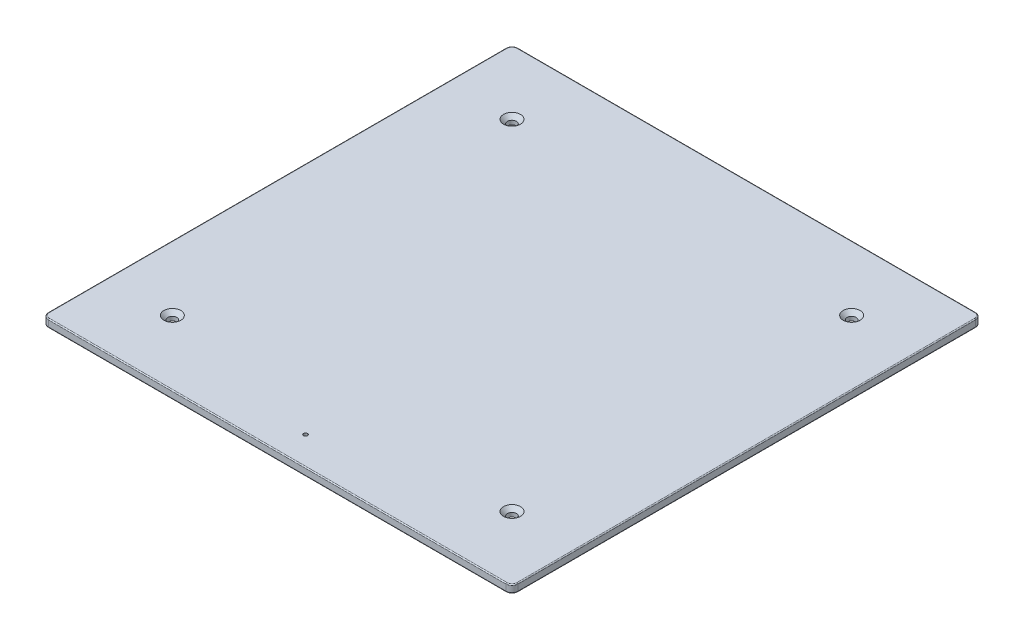
SolidWorks part; units mm, degrees
ref_plane "Front Plane" through (0, 0, 0) normal (0, 0, 1) x (1, 0, 0)
ref_plane "Top Plane" through (0, 0, 0) normal (0, 1, 0) x (1, 0, 0)
ref_plane "Right Plane" through (0, 0, 0) normal (1, 0, 0) x (0, 0, -1)
sketch "Sketch1" plane through (0, 0, 0) normal (0, 1, 0) x (1, 0, 0)
  line L1 (-117.5, 117.5) -> (117.5, 117.5)
  line L2 (-117.5, 117.5) -> (-117.5, -117.5)
  line L3 (-117.5, -117.5) -> (117.5, -117.5)
  line L4 (117.5, 117.5) -> (117.5, -117.5)
  line L5 (-117.5, 117.5) -> (117.5, -117.5) construction
  line L6 (-117.5, -117.5) -> (117.5, 117.5) construction
  circle A0 centre (85, 85) radius 2.25
  circle A1 centre (-85, 85) radius 2.25
  circle A2 centre (-85, -85) radius 2.25
  circle A3 centre (85, -85) radius 2.25
  point P0 (0, 0)
  dimension "D11" = 4.5
  dimension "D1" = 235
  dimension "D2" = 235
  dimension "D3" = 32.5
  dimension "D4" = 32.5
  dimension "D5" = 32.5
  dimension "D6" = 32.5
  dimension "D7" = 32.5
  dimension "D8" = 32.5
  dimension "D9" = 32.5
  dimension "D10" = 32.5
extrude "Boss-Extrude1" add sketch "Sketch1" along normal blind 4
chamfer "Chamfer1" distance 2 angle 45 4 edges at (-85, 4, 87.25) (85, 4, 87.25) (85, 4, -82.75) (-85, 4, -82.75)
fillet "Fillet1" radius 3 4 edges at (117.5, 2, 117.5) (-117.5, 2, 117.5) (-117.5, 2, -117.5) (117.5, 2, -117.5)
fillet "Fillet2" radius 0.5 16 edges at (116.6213, 0, -116.6213) (117.5, 0, 0) (116.6213, 0, 116.6213) (0, 0, 117.5) (-116.6213, 0, 116.6213) (-117.5, 0, 0) (-116.6213, 0, -116.6213) (-116.6213, 4, -116.6213) (0, 4, -117.5) (116.6213, 4, -116.6213) (117.5, 4, 0) (116.6213, 4, 116.6213) (0, 4, 117.5) (-116.6213, 4, 116.6213) (0, 0, -117.5) (-117.5, 4, 0)
sketch "Sketch2" plane through (0, 4, 0) normal (0, 1, 0) x (1, 0, 0)
  circle A0 centre (0, -103.3328) radius 1
  dimension "D1" = 2
extrude "Cut-Extrude1" cut sketch "Sketch2" against normal blind 4
